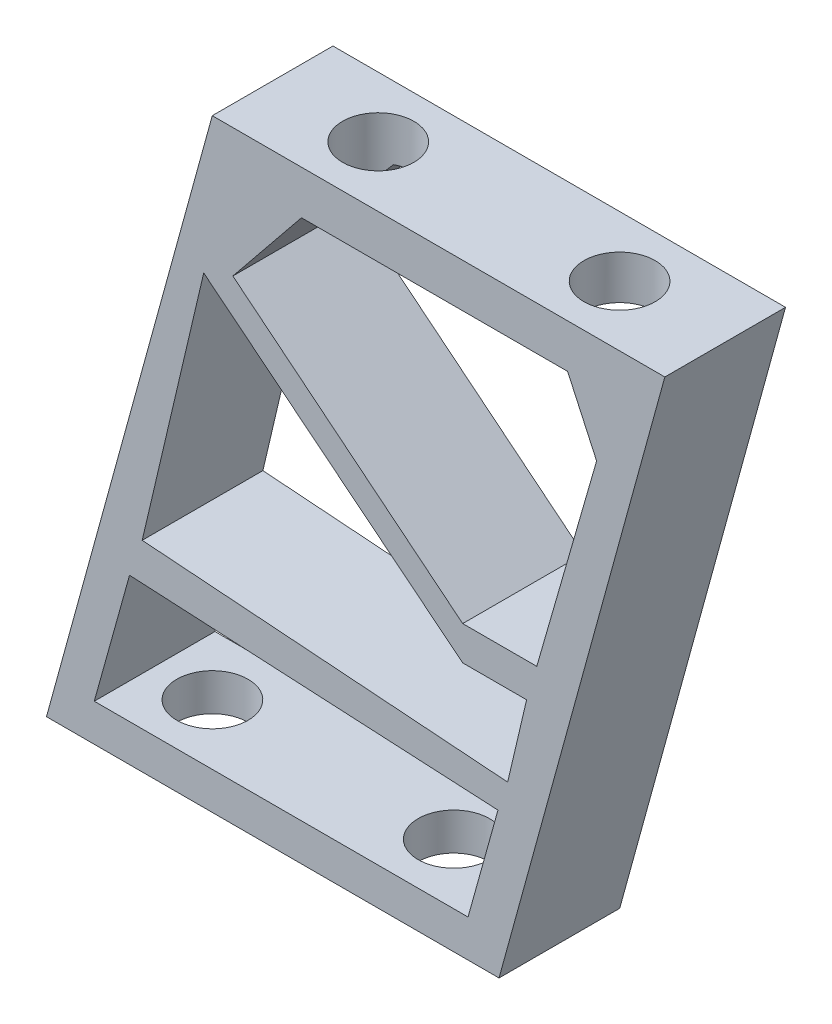
SolidWorks part; units mm, degrees
ref_plane "Front Plane" through (0, 0, 0) normal (0, 0, 1) x (1, 0, 0)
ref_plane "Top Plane" through (0, 0, 0) normal (0, 1, 0) x (1, 0, 0)
ref_plane "Right Plane" through (0, 0, 0) normal (1, 0, 0) x (0, 0, -1)
sketch "Sketch2" plane through (0, 0, 0) normal (0, 0, 1) x (1, 0, 0)
  line L0 (-7.7545, 6.8683) -> (11.2955, 6.8683)
  line L1 (11.2955, 6.8683) -> (4.3164, -18.5317)
  line L2 (4.3164, -18.5317) -> (-14.7336, -18.5317)
  line L3 (-14.7336, -18.5317) -> (-7.7545, 6.8683)
  dimension "D1" = 19.05
  dimension "D2" = 25.4
extrude "Boss-Extrude1" add sketch "Sketch2" along normal blind 5.08
sketch "Sketch3" plane through (0, 6.8683, 0) normal (0, 1, 0) x (1, 0, 0)
  line L0 (-7.7545, -2.54) -> (11.2955, -2.54) construction
  line L1 (-7.7545, -5.08) -> (-7.7545, 0) construction
  line L2 (11.2955, -5.08) -> (11.2955, 0) construction
  line L3 (1.7705, 0) -> (1.7705, -5.08) construction
  line L4 (11.2955, 0) -> (-7.7545, 0) construction
  line L5 (11.2955, -5.08) -> (-7.7545, -5.08) construction
  circle A2 centre (6.8505, -2.54) radius 1.5
  circle A3 centre (-3.3095, -2.54) radius 1.5
  dimension "D1" = 3
  dimension "D2" = 5.08
  dimension "D3" = 3
  dimension "D4" = 5.08
extrude "Cut-Extrude1" cut sketch "Sketch3" against normal blind 5.08
sketch "Sketch4" plane through (0, 0, 0) normal (0, 0, -1) x (-1, 0, 0)
  line L15 (-7.2036, 5.0255) -> (-8.4234, 2.3707)
  line L16 (-8.4234, 2.3707) -> (-5.9048, -6.3763)
  line L17 (-5.9048, -6.3763) -> (-2.7861, -6.3763)
  line L18 (-2.7861, -6.3763) -> (6.8891, 1.4556)
  line L19 (6.8891, 1.4556) -> (3.9994, 5.0255)
  line L20 (3.9994, 5.0255) -> (-7.2036, 5.0255)
  line L21 (8.1151, 0.956) -> (10.7043, -10.0861)
  line L22 (10.7043, -10.0861) -> (-4.6795, -11.2092)
  line L23 (-4.6795, -11.2092) -> (-5.4768, -7.8091)
  line L24 (-5.4768, -7.8091) -> (-2.7861, -7.8091)
  line L25 (-2.7861, -7.8091) -> (8.1151, 0.956)
  line L26 (-4.2711, -12.4345) -> (-3.0118, -16.9612)
  line L27 (-3.0118, -16.9612) -> (12.7218, -16.9612)
  line L28 (12.7218, -16.9612) -> (11.2373, -11.6249)
  line L29 (11.2373, -11.6249) -> (-4.2711, -12.4345)
extrude "Cut-Extrude2" cut sketch "Sketch4" against normal blind 7.62
sketch "Sketch5" plane through (0, -18.5317, 0) normal (0, -1, 0) x (1, 0, 0)
  line L0 (4.3164, 2.54) -> (-14.7336, 2.54) construction
  line L1 (4.3164, 5.08) -> (4.3164, 0) construction
  line L2 (-14.7336, 5.08) -> (-14.7336, 0) construction
  line L3 (-5.2086, 0) -> (-5.2086, 5.08) construction
  line L4 (-14.7336, 0) -> (4.3164, 0) construction
  line L5 (-14.7336, 5.08) -> (4.3164, 5.08) construction
  circle A0 centre (-0.1286, 2.54) radius 1.5
  circle A1 centre (-10.2886, 2.54) radius 1.5
  dimension "D1" = 3
  dimension "D2" = 5.08
  dimension "D3" = 5.08
extrude "Cut-Extrude3" cut sketch "Sketch5" against normal blind 2.54
